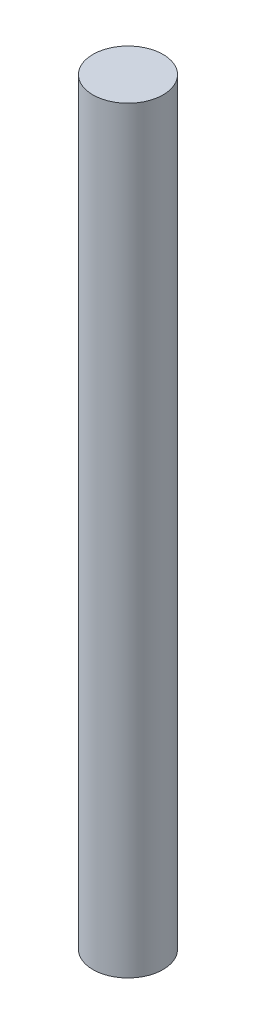
SolidWorks part; units mm, degrees
ref_plane "前视基准面" through (0, 0, 0) normal (0, 0, 1) x (1, 0, 0)
ref_plane "上视基准面" through (0, 0, 0) normal (0, 1, 0) x (1, 0, 0)
ref_plane "右视基准面" through (0, 0, 0) normal (1, 0, 0) x (0, 0, -1)
sketch "草图1" plane through (0, 0, 0) normal (0, 1, 0) x (1, 0, 0)
  circle A0 centre (0, 0) radius 25
  dimension "D1" = 50
extrude "凸台-拉伸1" add sketch "草图1" along normal blind 540
